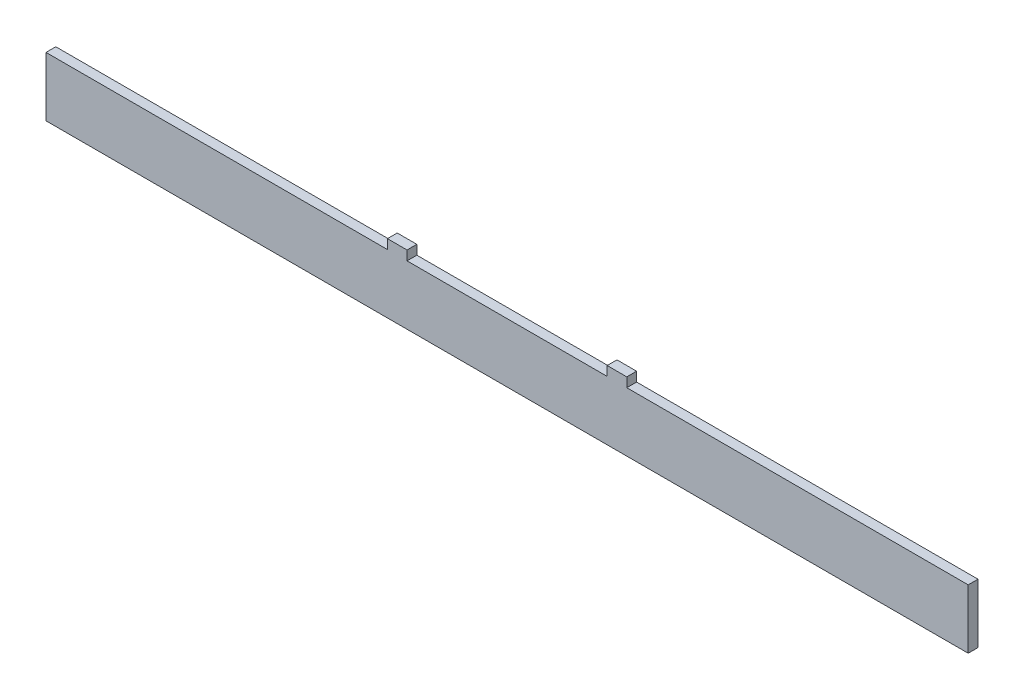
SolidWorks part; units mm, degrees
ref_plane "Front Plane" through (0, 0, 0) normal (0, 0, 1) x (1, 0, 0)
ref_plane "Top Plane" through (0, 0, 0) normal (0, 1, 0) x (1, 0, 0)
ref_plane "Right Plane" through (0, 0, 0) normal (1, 0, 0) x (0, 0, -1)
sketch "Sketch1" plane through (0, 0, 0) normal (0, 1, 0) x (1, 0, 0)
  line L1 (-149.225, -1.5875) -> (149.225, -1.5875)
  line L2 (-149.225, -1.5875) -> (-149.225, 1.5875)
  line L3 (-149.225, 1.5875) -> (149.225, 1.5875)
  line L4 (149.225, -1.5875) -> (149.225, 1.5875)
  line L5 (-149.225, -1.5875) -> (149.225, 1.5875) construction
  line L6 (-149.225, 1.5875) -> (149.225, -1.5875) construction
  point P0 (0, 0)
  dimension "D1" = 298.45
  dimension "D2" = 3.175
extrude "Boss-Extrude1" add sketch "Sketch1" along normal blind 22.225
sketch "Sketch2" plane through (0, 0, 1.5875) normal (0, 0, 1) x (1, 0, 0)
  line L0 (-149.225, 22.225) -> (149.225, 22.225) construction
  line L1 (-149.225, 22.225) -> (-38.735, 22.225)
  line L2 (-149.225, 22.225) -> (-149.225, 19.177)
  line L3 (-149.225, 19.177) -> (-38.735, 19.177)
  line L4 (-38.735, 22.225) -> (-38.735, 19.177)
  line L5 (149.225, 22.225) -> (38.735, 22.225)
  line L6 (149.225, 22.225) -> (149.225, 19.177)
  line L7 (149.225, 19.177) -> (38.735, 19.177)
  line L8 (38.735, 22.225) -> (38.735, 19.177)
  line L9 (32.385, 19.177) -> (-32.385, 19.177)
  line L10 (32.385, 19.177) -> (32.385, 22.225)
  line L11 (32.385, 22.225) -> (-32.385, 22.225)
  line L12 (-32.385, 19.177) -> (-32.385, 22.225)
  line L13 (-38.735, 22.225) -> (-32.385, 22.225) construction
  line L14 (32.385, 22.225) -> (38.735, 22.225) construction
  dimension "D1" = 64.77
  dimension "D2" = 6.35
  dimension "D3" = 3.048
extrude "Cut-Extrude1" cut sketch "Sketch2" against normal through all
